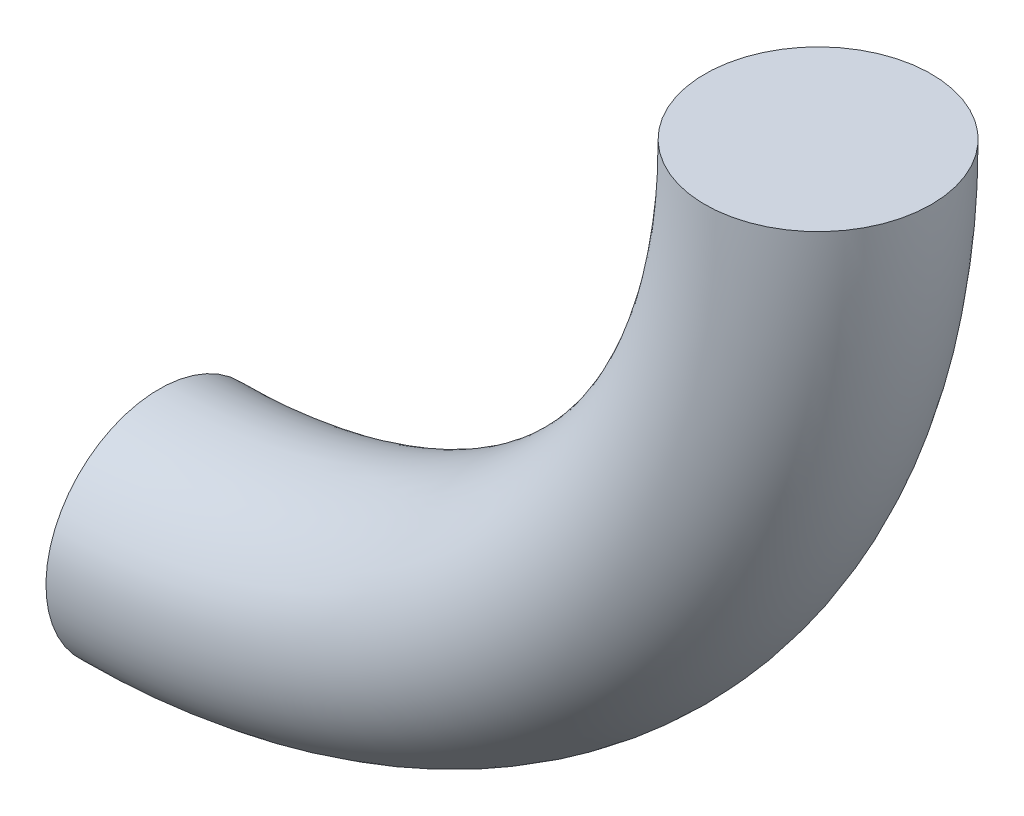
SolidWorks part; units mm, degrees
ref_plane "Front Plane" through (0, 0, 0) normal (0, 0, 1) x (1, 0, 0)
ref_plane "Top Plane" through (0, 0, 0) normal (0, 1, 0) x (1, 0, 0)
ref_plane "Right Plane" through (0, 0, 0) normal (1, 0, 0) x (0, 0, -1)
sketch "SweepSection" plane through (0, 0, 0) normal (1, 0, 0) x (0, 0, -1)
  circle A0 centre (0, 0) radius 7.093
  dimension "D1" = 14.186
sketch "SweepPath" plane through (0, 0, 0) normal (0, 0, 1) x (1, 0, 0)
  arc A0 (0, 0) -> (41.297, 41.297) centre (0, 41.297) ccw
  dimension "D1" = 41.297
sweep "OrdinarySweptBoss" add profiles "SweepSection" path "SweepPath"
